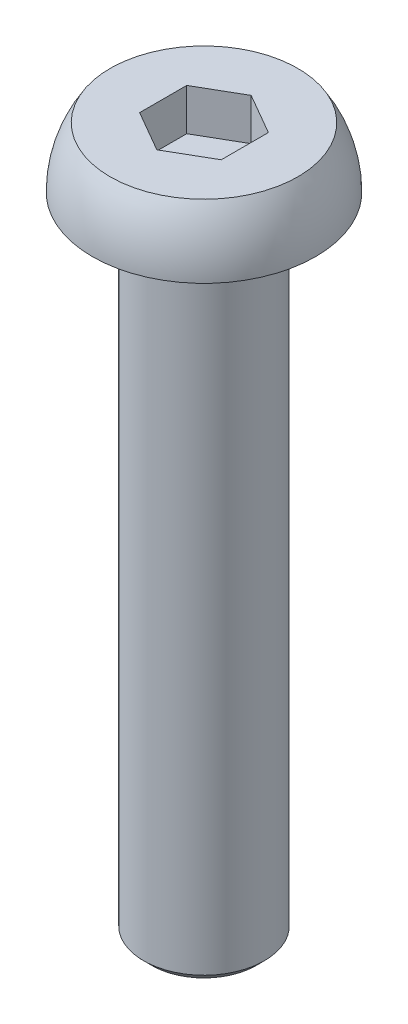
SolidWorks part; units mm, degrees
material "AISI 304"
ref_plane "前视基准面" through (0, 0, 0) normal (0, 0, 1) x (1, 0, 0)
ref_plane "上视基准面" through (0, 0, 0) normal (0, 1, 0) x (1, 0, 0)
ref_plane "右视基准面" through (0, 0, 0) normal (1, 0, 0) x (0, 0, -1)
sketch "草图1" plane through (0, 0, 0) normal (0, 0, 1) x (1, 0, 0)
  line L0 (0, 5.1118) -> (0, 0) construction
  line L1 (0, 0) -> (-2.775, 0)
  line L2 (-2.3347, 1.5) -> (0, 1.5)
  line L3 (0, 1.5) -> (0, 0)
  arc A1 (-2.3347, 1.5) -> (-2.775, 0) centre (0, 0) ccw
  dimension "D2" = 5.55
  dimension "D1" = 1.5
revolve "旋转1" add sketch "草图1" angle 360 about L0
sketch "草图2" plane through (0, 0, 0) normal (0, -1, 0) x (1, 0, 0)
  circle A0 centre (0, 0) radius 1.5
  dimension "D1" = 3
extrude "凸台-拉伸1" add sketch "草图2" along normal blind 16
sketch "草图3" plane through (0, 1.5, 0) normal (0, 1, 0) x (1, 0, 0)
  line L0 (0, 1.172) -> (-1.015, 0.586)
  line L1 (-1.015, 0.586) -> (-1.015, -0.586)
  line L2 (-1.015, -0.586) -> (0, -1.172)
  line L3 (0, -1.172) -> (1.015, -0.586)
  line L4 (1.015, -0.586) -> (1.015, 0.586)
  line L5 (1.015, 0.586) -> (0, 1.172)
  dimension "D1" = 2.03
extrude "切除-拉伸1" cut sketch "草图3" against normal blind 1.04
chamfer "倒角1" distance 0.2 angle 45 1 edges at (0, -16, -1.5)
